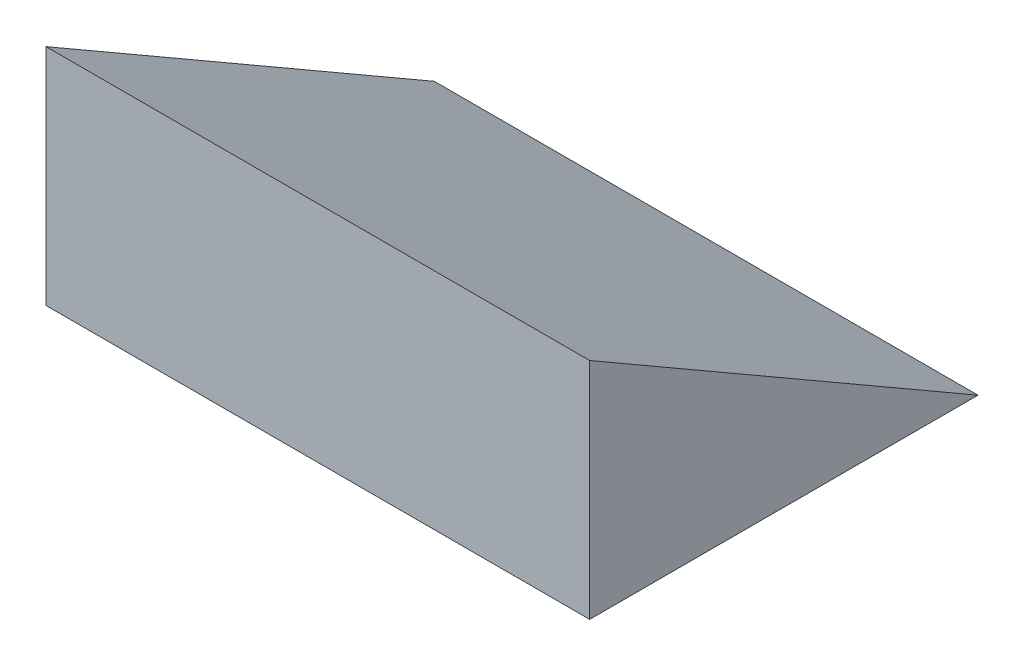
SolidWorks part; units mm, degrees
ref_plane "Front Plane" through (0, 0, 0) normal (0, 0, 1) x (1, 0, 0)
ref_plane "Top Plane" through (0, 0, 0) normal (0, 1, 0) x (1, 0, 0)
ref_plane "Right Plane" through (0, 0, 0) normal (1, 0, 0) x (0, 0, -1)
sketch "Sketch1" plane through (0, 0, 0) normal (1, 0, 0) x (0, 0, -1)
  line L0 (0, 0) -> (10, 0)
  line L1 (10, 0) -> (0, 5.7735)
  line L2 (0, 5.7735) -> (0, 0)
  dimension "D1" = 30
  dimension "D2" = 10
extrude "Boss-Extrude1" add sketch "Sketch1" along normal blind 14
